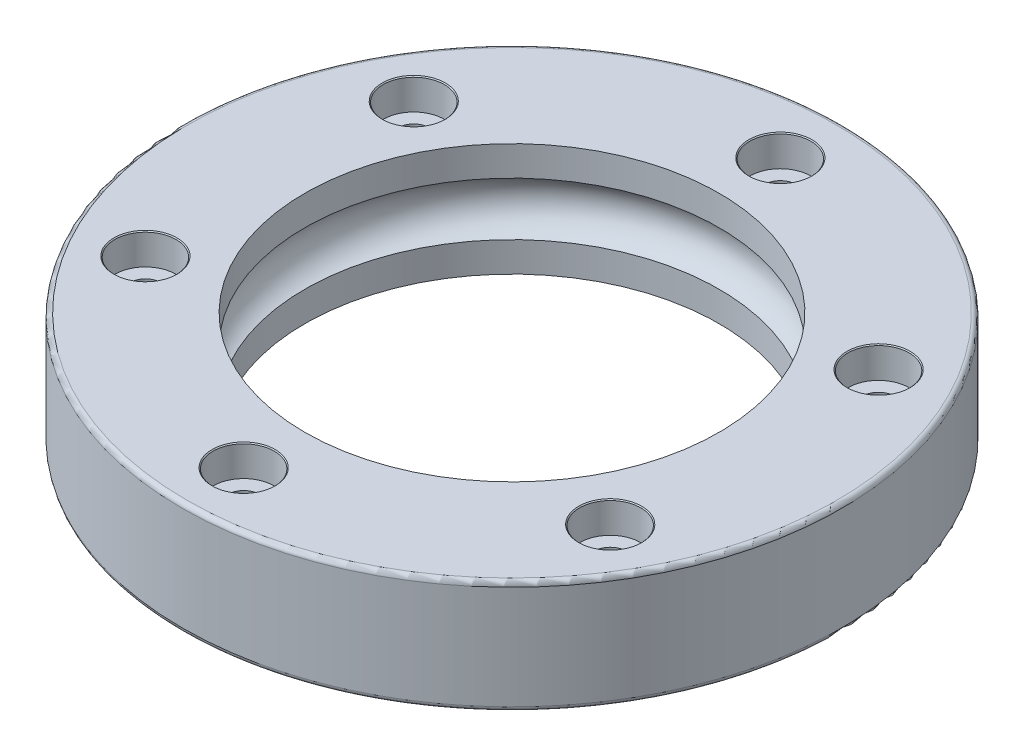
SolidWorks part; units mm, degrees
material "合金钢"
ref_plane "前视基准面" through (0, 0, 0) normal (0, 0, 1) x (1, 0, 0)
ref_plane "上视基准面" through (0, 0, 0) normal (0, 1, 0) x (1, 0, 0)
ref_plane "右视基准面" through (0, 0, 0) normal (1, 0, 0) x (0, 0, -1)
sketch "草图1" plane through (0, 0, 0) normal (0, 0, 1) x (1, 0, 0)
  line L0 (0, 15.877) -> (0, -17.1768) construction
  line L1 (-24.7903, 0) -> (25.4403, 0) construction
  line L2 (-22, 6) -> (-22, 2.8284)
  line L3 (-22, 6) -> (-35, 6)
  line L4 (-35, 6) -> (-35, -6)
  line L5 (-22, -6) -> (-35, -6)
  line L6 (-22, -6) -> (-22, -2.8284)
  arc A0 (-22, 2.8284) -> (-22, -2.8284) centre (-21, 0) ccw
  point P11 (-35, 0)
  dimension "D1" = 3
  dimension "D2" = 1
  dimension "D3" = 12
  dimension "D4" = 44
  dimension "D5" = 70
revolve "旋转1" add sketch "草图1" angle 360 about L0
fillet "圆角1" radius 0.5 2 edges at (0, -6, 35) (0, 6, 35)
sketch "草图2" plane through (0, 6, 0) normal (0, 1, 0) x (1, 0, 0)
  circle A0 centre (0, 0) radius 28.5 construction
  circle A1 centre (0, 28.5) radius 1.7
  circle A2 centre (24.6817, 14.25) radius 1.7
  circle A3 centre (24.6817, -14.25) radius 1.7
  circle A4 centre (0, -28.5) radius 1.7
  circle A5 centre (-24.6817, -14.25) radius 1.7
  circle A6 centre (-24.6817, 14.25) radius 1.7
  point P17 (0, 0)
  dimension "D1" = 57
  dimension "D2" = 3.4
  dimension "D3" = 6
extrude "切除-拉伸1" cut sketch "草图2" against normal blind 20
sketch "草图3" plane through (0, 6, 0) normal (0, 1, 0) x (1, 0, 0)
  circle A0 centre (0, 28.5) radius 3.25
  circle A1 centre (24.6817, 14.25) radius 3.25
  circle A2 centre (24.6817, -14.25) radius 3.25
  circle A3 centre (0, -28.5) radius 3.25
  circle A4 centre (-24.6817, -14.25) radius 3.25
  circle A5 centre (-24.6817, 14.25) radius 3.25
  point P16 (0, 0)
  dimension "D1" = 6.5
  dimension "D2" = 6
extrude "切除-拉伸2" cut sketch "草图3" against normal blind 3.3
chamfer "倒角1" distance 0.1 angle 45 6 edges at (24.6817, 6, 17.5) (24.6817, 6, -11) (0, 6, -25.25) (-24.6817, 6, -11) (-24.6817, 6, 17.5) (0, 6, 31.75)
